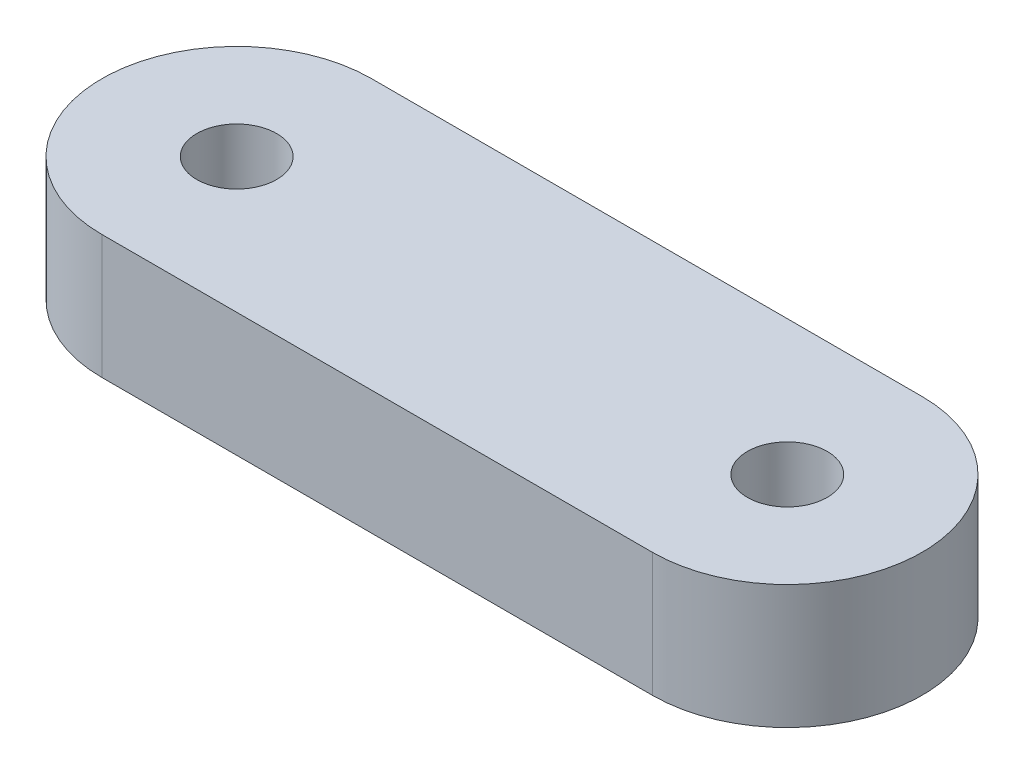
SolidWorks part; units mm, degrees
ref_plane "Front Plane" through (0, 0, 0) normal (0, 0, 1) x (1, 0, 0)
ref_plane "Top Plane" through (0, 0, 0) normal (0, 1, 0) x (1, 0, 0)
ref_plane "Right Plane" through (0, 0, 0) normal (1, 0, 0) x (0, 0, -1)
sketch "Sketch1" plane through (0, 0, 0) normal (0, 1, 0) x (1, 0, 0)
  line L0 (14.9, 0) -> (14.9, 15.5804) construction
  line L1 (-10, 4.9) -> (10, 4.9)
  line L2 (-14.9, 0) -> (-14.9, 15.5804) construction
  line L3 (-10, -4.9) -> (10, -4.9)
  line L4 (-10, 4.9) -> (-10, -4.9) construction
  line L5 (-10, 4.9) -> (10, -4.9) construction
  line L6 (-10, -4.9) -> (10, 4.9) construction
  line L7 (10, 4.9) -> (10, -4.9) construction
  line L8 (0, 4.9) -> (0, -4.9) construction
  arc A0 (-10, 4.9) -> (-10, -4.9) centre (-10, 0) ccw
  arc A1 (10, -4.9) -> (10, 4.9) centre (10, 0) ccw
  circle A2 centre (-10, 0) radius 1.45
  circle A3 centre (10, 0) radius 1.45
  point P0 (0, 0)
  dimension "D4" = 4.9
  dimension "D5" = 2.9
  dimension "D1" = 9.8
  dimension "D2" = 20
extrude "Boss-Extrude1" add sketch "Sketch1" along normal blind 4.5
equation "\"Y-ROD-SPACING\"=75"
equation "\"Y-BED-OFFSET\"=2"
equation "\"Y-BED-ROD-INSET\"=3.5"
equation "\"T-SLOT-NUT-FILLET-RADIUS\"=0.5"
equation "\"T-SLOT-SCREW-SHAFT-RADIUS\"=1.55"
equation "\"T-SLOT-SCREW-SHAFT-CUTOUT-LENGTH\"=11.0"
equation "\"T-SLOT-NUT-DEPTH\"=3.5"
equation "\"T-SLOT-NUT-WIDTH\"=2.85"
equation "\"T-SLOT-NUT-END-DISTANCE\"=8"
equation "\"ACRYLIC-TAB-CUTOUT-SIZE\"=\"ACRYLIC-THICKNESS\"+\"ACRYLIC-TAB-TOLERANCE\"*2"
equation "\"ACRYLIC-M3-HOLE\"=2.9"
equation "\"D5@Sketch1\"=\"ACRYLIC-M3-HOLE\""
equation "\"SMOOTHROD-CAP-SCREW-DISTANCE\"=20"
equation "\"D2@Sketch1\"=\"SMOOTHROD-CAP-SCREW-DISTANCE\""
equation "\"X-ROD-SPACING\"=45"
equation "\"Z-ROD-SPACING\"=17.5"
equation "\"ACRYLIC-THICKNESS\"=10"
equation "\"ACRYLIC-THICKNESS2\"=4.5"
equation "\"ACRYLIC-TAB-WIDTH\"=\"ACRYLIC-THICKNESS\""
equation "\"FRAME-WIDTH-INNER\"=370"
equation "\"NEMA17-HOLE-SPACING\"=31"
equation "\"NEMA17-CENTRAL-CUTOUT\"=22.5"
equation "\"Z-BRACKET-REACH\"=55"
equation "\"TOP-BRACKET-SPACING\"=40"
equation "\"SMOOTHROD-X-LENGTH\"=350"
equation "\"SMOOTHROD-Y-LENGTH\"=350"
equation "\"SMOOTHROD-Z-LENGTH\"=350"
equation "\"SMOOTHROD-TIGHTENING-HEADROOM\"=.25"
equation "\"LEADSCREW-Z-LENGTH\"=300"
equation "\"SCREW-LENGTH-FRAME\"=\"ACRYLIC-THICKNESS\" + 10"
equation "\"SCREW-HEAD-RADIUS\"=6"
equation "\"PRINTED-X-SMOOTHROD-DIAMETER\"=8.4"
equation "\"PRINTED-X-SMOOTHROD-CUTOUT\"=10"
equation "\"PRINTED-X-BASE-HEIGHT\"=10"
equation "\"PRINTED-LM8UU-CUTOUT-SIZE\"=15.5"
equation "\"PRINTED-LM8UU-CUTOUT-LENGTH\"=24.5"
equation "\"PRINTED-X-IDLER-HEIGHT\"=16"
equation "\"PSU-MOUNTING-WIDTH\"=95"
equation "\"PSU-MOUNTING-HEIGHT\"=177"
equation "\"D1@Boss-Extrude1\"=\"ACRYLIC-THICKNESS2\""
